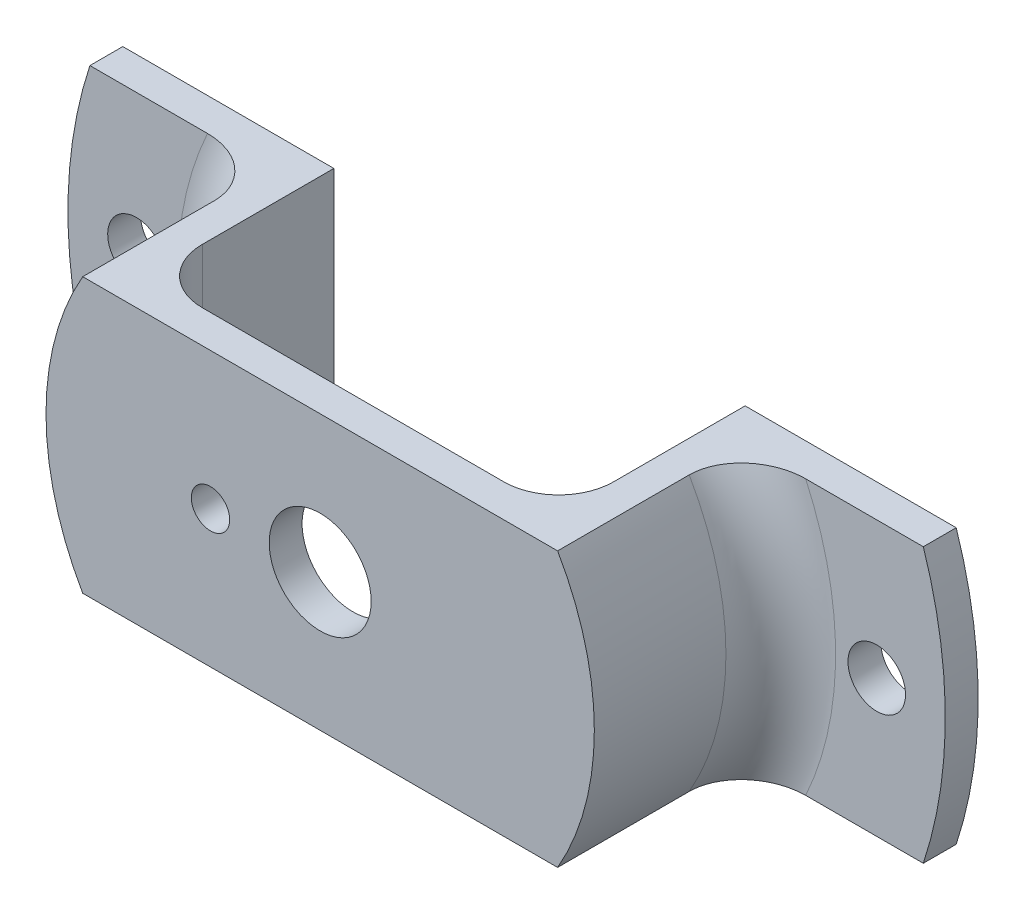
SolidWorks part; units mm, degrees
ref_plane "Front Plane" through (0, 0, 0) normal (0, 0, 1) x (1, 0, 0)
ref_plane "Top Plane" through (0, 0, 0) normal (0, 1, 0) x (1, 0, 0)
ref_plane "Right Plane" through (0, 0, 0) normal (1, 0, 0) x (0, 0, -1)
sketch "Sketch1" plane through (0, 0, 0) normal (0, 0, 1) x (1, 0, 0)
  line L1 (-28.75, 12.5) -> (28.75, 12.5)
  line L2 (-28.75, 12.5) -> (-28.75, -12.5)
  line L3 (-28.75, -12.5) -> (28.75, -12.5)
  line L4 (28.75, 12.5) -> (28.75, -12.5)
  line L5 (-28.75, 12.5) -> (28.75, -12.5) construction
  line L6 (-28.75, -12.5) -> (28.75, 12.5) construction
  circle A0 centre (0, 0) radius 4.65
  circle A1 centre (-10, 0) radius 1.75
  point P0 (0, 0)
  dimension "D3" = 9.3
  dimension "D4" = 3.5
  dimension "D1" = 25
  dimension "D2" = 57.5
  dimension "D5" = 10
extrude "Boss-Extrude1" add sketch "Sketch1" along normal blind 3
sketch "Sketch2" plane through (0, 0, 0) normal (0, 0, -1) x (-1, 0, 0)
  line L0 (28.75, -12.5) -> (-28.75, -12.5) construction
  line L1 (-28.75, 12.5) -> (-18.75, 12.5)
  line L2 (-28.75, 12.5) -> (-28.75, -12.5)
  line L3 (-28.75, -12.5) -> (-18.75, -12.5)
  line L4 (-18.75, 12.5) -> (-18.75, -12.5)
  dimension "D1" = 10
extrude "Boss-Extrude2" add sketch "Sketch2" along normal blind 17
sketch "Sketch4" plane through (28.75, 0, 0) normal (1, 0, 0) x (0, 0, -1)
  line L0 (-3, -12.5) -> (17, -12.5) construction
  line L1 (17, 12.5) -> (14, 12.5)
  line L2 (17, 12.5) -> (17, -12.5)
  line L3 (17, -12.5) -> (14, -12.5)
  line L4 (14, 12.5) -> (14, -12.5)
  dimension "D1" = 3
extrude "Boss-Extrude3" add sketch "Sketch4" along normal blind 15
mirror "Mirror2" about plane through (0, 0, 0) normal (1, 0, 0) of "Boss-Extrude2"
mirror "Mirror3" about plane through (0, 0, 0) normal (1, 0, 0) of "Boss-Extrude3"
sketch "Sketch8" plane through (0, 0, -17) normal (0, 0, -1) x (-1, 0, 0)
  circle A0 centre (0, 0) radius 40
  circle A1 centre (0, 0) radius 69.6687
  dimension "D1" = 80
extrude "Cut-Extrude3" cut sketch "Sketch8" against normal blind 40
sketch "Sketch9" plane through (0, 0, -14) normal (0, 0, 1) x (1, 0, 0)
  circle A0 centre (0, 0) radius 33.75 construction
  circle A1 centre (-33.75, 0) radius 2.625
  circle A2 centre (33.75, 0) radius 2.625
  dimension "D1" = 5.25
  dimension "D2" = 5.25
extrude "Cut-Extrude4" cut sketch "Sketch9" against normal mid plane 10
sketch "Sketch7" plane through (0, 0, -17) normal (0, 0, -1) x (-1, 0, 0)
  circle A0 centre (0, 0) radius 30.1743
sketch "Sketch10" plane through (0, 0, -17) normal (0, 0, -1) x (-1, 0, 0)
  circle A0 centre (0, 0) radius 27.5
  dimension "D1" = 55
sketch "Sketch11" plane through (0, 0, 3) normal (0, 0, 1) x (1, 0, 0)
  circle A2 centre (0, 0) radius 25
  circle A3 centre (0, 0) radius 34.6411
  dimension "D1" = 50
extrude "Cut-Extrude5" cut sketch "Sketch11" against normal blind 17
fillet "Fillet1" radius 5 4 edges at (25, 0, -14) (-25, 0, -14) (18.75, 0, 0) (-18.75, 0, 0)
